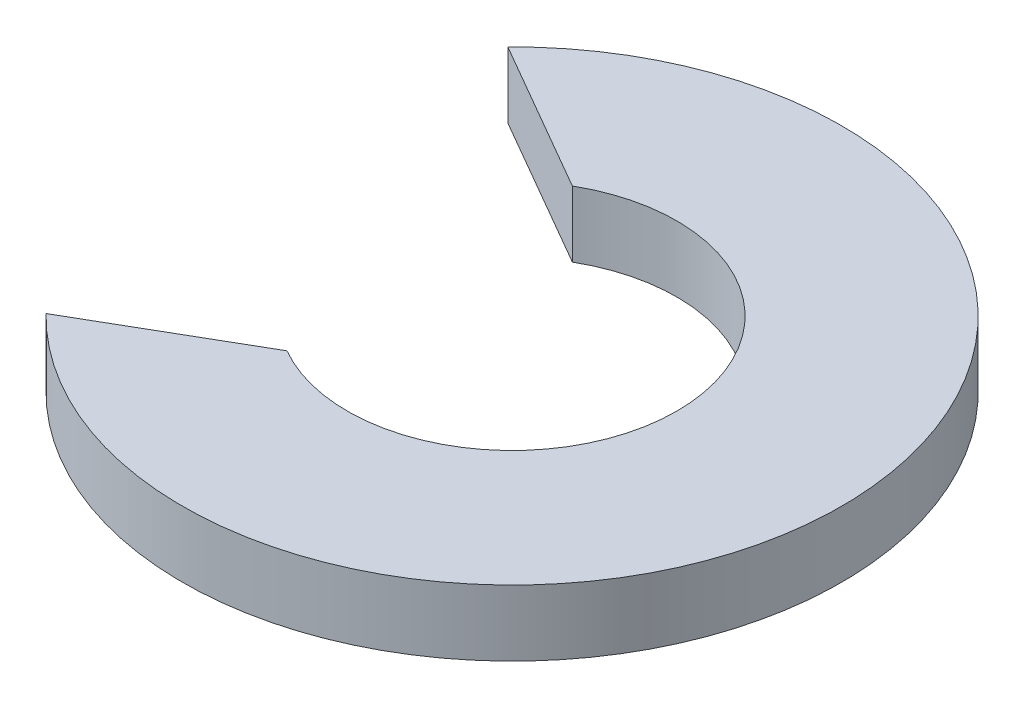
SolidWorks part; units mm, degrees
ref_plane "前视基准面" through (0, 0, 0) normal (0, 0, 1) x (1, 0, 0)
ref_plane "上视基准面" through (0, 0, 0) normal (0, 1, 0) x (1, 0, 0)
ref_plane "右视基准面" through (0, 0, 0) normal (1, 0, 0) x (0, 0, -1)
other "Configuration Table"
sketch "草图1" plane through (0, 0, 0) normal (0, 1, 0) x (1, 0, 0)
  line L0 (-1, 1.7321) -> (-2.8541, 2.8025)
  line L1 (-4.5472, 0) -> (7.0944, 0) construction
  line L2 (0, 3.5881) -> (0, -3.9683) construction
  line L3 (-1, -1.7321) -> (-2.8541, -2.8025)
  arc A0 (-1, -1.7321) -> (-1, 1.7321) centre (0, 0) ccw
  arc A1 (-2.8541, -2.8025) -> (-2.8541, 2.8025) centre (0, 0) ccw
  dimension "D1" = 4
  dimension "D2" = 8
  dimension "D3" = 30
  dimension "D4" = 1
extrude "凸台-拉伸1" add sketch "草图1" along normal blind 0.8
